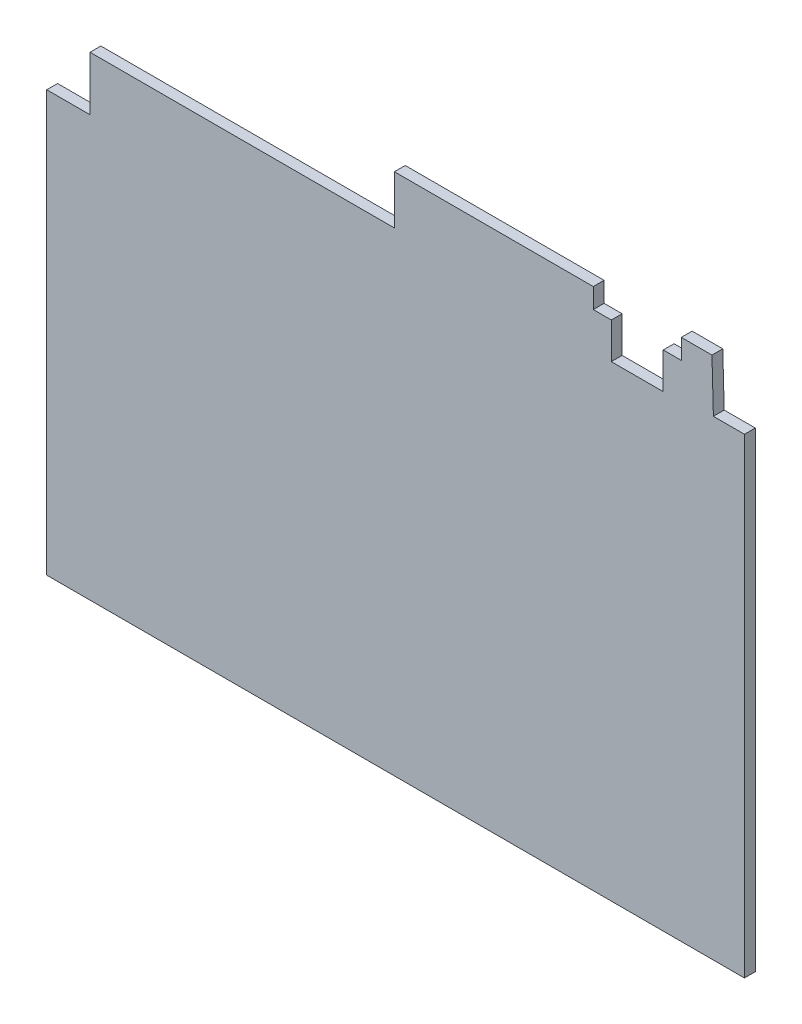
SolidWorks part; units mm, degrees
material "Pine"
ref_plane "Front Plane" through (0, 0, 0) normal (0, 0, 1) x (1, 0, 0)
ref_plane "Top Plane" through (0, 0, 0) normal (0, 1, 0) x (1, 0, 0)
ref_plane "Right Plane" through (0, 0, 0) normal (1, 0, 0) x (0, 0, -1)
sketch "Sketch1" plane through (0, 0, 0) normal (0, 0, 1) x (1, 0, 0)
  line L0 (28.5714, 236.0602) -> (28.5714, 237.0518)
  line L1 (28.5714, 277.1048) -> (28.5714, -22.8952) construction
  line L2 (28.5714, 237.0518) -> (5.4155, 237.0518)
  line L3 (5.4155, 237.0518) -> (4.5714, 268.1048)
  line L4 (4.5714, 268.1048) -> (-12.4286, 268.1048)
  line L5 (-12.4286, 268.1048) -> (-12.4286, 237.0518)
  line L6 (-12.4286, 237.0518) -> (-38.2166, 237.0518)
  line L7 (-38.2166, 237.0518) -> (-38.2166, 268.1048)
  line L8 (-221.4286, 268.1048) -> (28.5714, 268.1048) construction
  line L9 (-38.2166, 268.1048) -> (-171.4286, 268.1048)
  line L10 (-171.4286, 268.1048) -> (-171.4286, 241.1048)
  line L11 (-171.4286, 241.1048) -> (-370.1235, 241.1048)
  line L12 (-370.1235, 241.1048) -> (-370.1235, -22.8952)
  line L13 (-370.1235, -22.8952) -> (28.5714, -22.8952)
  line L14 (28.5714, -22.8952) -> (28.5714, 236.0602)
extrude "Boss-Extrude1" add sketch "Sketch1" along normal blind 6
sketch "Sketch2" plane through (0, 0, 6) normal (0, 0, 1) x (1, 0, 0)
  line L1 (-370.1235, 241.1048) -> (-340.1235, 241.1048)
  line L2 (-370.1235, 241.1048) -> (-370.1235, 211.1048)
  line L3 (-370.1235, 211.1048) -> (-340.1235, 211.1048)
  line L4 (-340.1235, 241.1048) -> (-340.1235, 211.1048)
  dimension "D1" = 30
  dimension "D2" = 30
extrude "Cut-Extrude1" cut sketch "Sketch2" against normal blind 10
sketch "Sketch3" plane through (0, 0, 6) normal (0, 0, 1) x (1, 0, 0)
  line L0 (28.5714, -22.8952) -> (28.5714, 237.0518) construction
  line L1 (-370.1235, -22.8952) -> (28.5714, -22.8952)
  line L2 (-370.1235, -22.8952) -> (-370.1235, -21.8952)
  line L3 (-370.1235, -21.8952) -> (28.5714, -21.8952)
  line L4 (28.5714, -22.8952) -> (28.5714, -21.8952)
  dimension "D1" = 1
extrude "Cut-Extrude2" cut sketch "Sketch3" against normal blind 10
sketch "Sketch4" plane through (0, 0, 6) normal (0, 0, 1) x (1, 0, 0)
  line L0 (-370.1235, 211.1048) -> (-340.1235, 211.1048) construction
  line L1 (-370.1235, -21.8952) -> (-364.1235, -21.8952)
  line L2 (-370.1235, -21.8952) -> (-370.1235, 211.1048)
  line L3 (-370.1235, 211.1048) -> (-364.1235, 211.1048)
  line L4 (-364.1235, -21.8952) -> (-364.1235, 211.1048)
  line L5 (28.5714, 237.0518) -> (5.4155, 237.0518) construction
  line L6 (28.5714, -21.8952) -> (22.5714, -21.8952)
  line L7 (28.5714, -21.8952) -> (28.5714, 237.0518)
  line L8 (28.5714, 237.0518) -> (22.5714, 237.0518)
  line L9 (22.5714, -21.8952) -> (22.5714, 237.0518)
  dimension "D1" = 6
  dimension "D2" = 6
extrude "Cut-Extrude3" cut sketch "Sketch4" against normal blind 10
sketch "Sketch5" plane through (0, 0, 6) normal (0, 0, 1) x (1, 0, 0)
  line L0 (-38.2166, 268.1048) -> (-171.4286, 268.1048) construction
  line L1 (-38.2166, 237.0518) -> (-61.2166, 237.0518)
  line L2 (-38.2166, 237.0518) -> (-38.2166, 268.1048)
  line L3 (-38.2166, 268.1048) -> (-61.2166, 268.1048)
  line L4 (-61.2166, 237.0518) -> (-61.2166, 268.1048)
  dimension "D1" = 23
extrude "Cut-Extrude4" cut sketch "Sketch5" against normal blind 10
sketch "Sketch6" plane through (0, 0, 6) normal (0, 0, 1) x (1, 0, 0)
  line L1 (-12.4286, 237.0518) -> (-22.4286, 237.0518)
  line L2 (-12.4286, 237.0518) -> (-12.4286, 257.0518)
  line L3 (-12.4286, 257.0518) -> (-22.4286, 257.0518)
  line L4 (-22.4286, 237.0518) -> (-22.4286, 257.0518)
  line L5 (-61.2166, 237.0518) -> (-51.2166, 237.0518)
  line L6 (-61.2166, 237.0518) -> (-61.2166, 257.0518)
  line L7 (-61.2166, 257.0518) -> (-51.2166, 257.0518)
  line L8 (-51.2166, 237.0518) -> (-51.2166, 257.0518)
  dimension "D1" = 20
  dimension "D2" = 20
  dimension "D3" = 10
  dimension "D4" = 10
extrude "Boss-Extrude2" add sketch "Sketch6" against normal up to vertex (6 mm away)
sketch "Sketch7" plane through (0, 0, 6) normal (0, 0, 1) x (1, 0, 0)
  line L0 (5.4155, 237.0518) -> (4.5714, 268.1048) construction
  line L1 (22.5714, 237.0518) -> (5.3598, 237.0518)
  line L2 (22.5714, 237.0518) -> (22.5714, 239.1018)
  line L3 (22.5714, 239.1018) -> (5.3598, 239.1018)
  line L4 (5.3598, 237.0518) -> (5.3598, 239.1018)
  dimension "D1" = 2.05
extrude "Boss-Extrude3" add sketch "Sketch7" against normal up to vertex (6 mm away)
